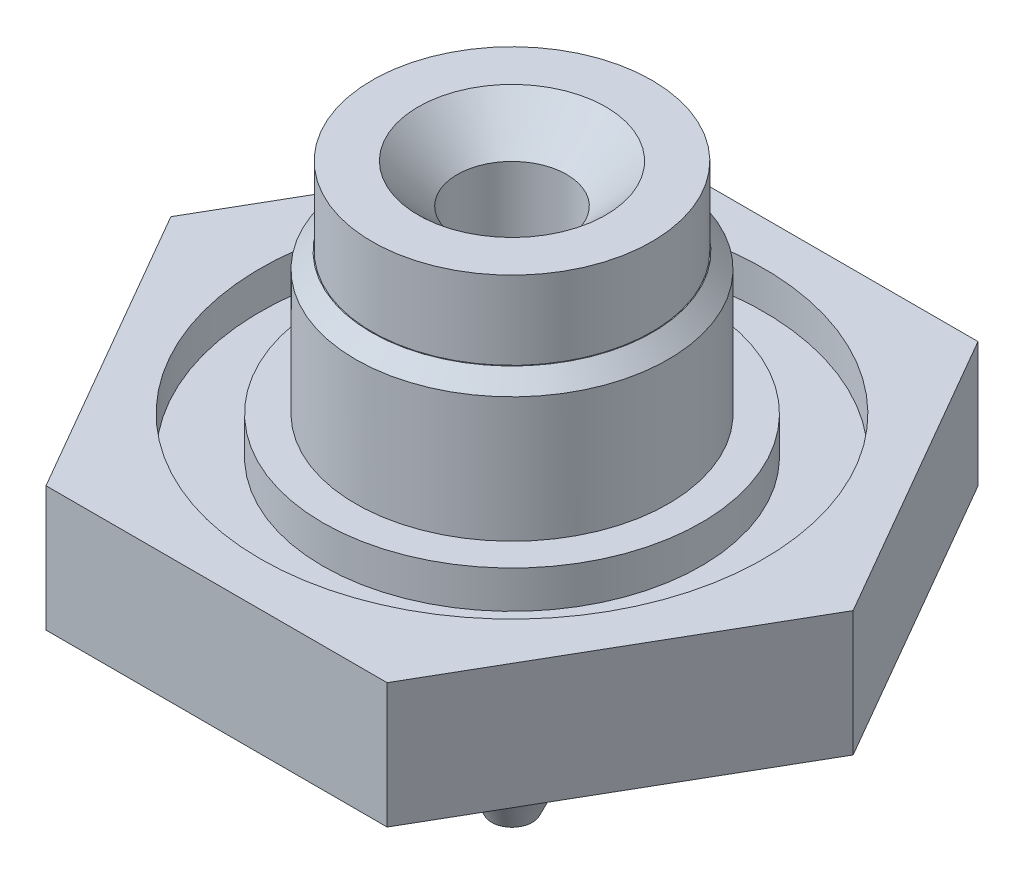
SolidWorks part; units mm, degrees
material "Acier allié inoxydable"
ref_plane "Front" through (0, 0, 0) normal (0, 0, 1) x (1, 0, 0)
ref_plane "Top" through (0, 0, 0) normal (0, 1, 0) x (1, 0, 0)
ref_plane "Right" through (0, 0, 0) normal (1, 0, 0) x (0, 0, -1)
sketch "Esquisse1" plane through (0, 0, 0) normal (0, 0, 1) x (1, 0, 0)
  line L0 (0, 0) -> (0, 18) construction
  line L1 (0.65, 0) -> (0.65, 2.5)
  line L2 (0.65, 2.5) -> (1.75, 3.6)
  line L3 (1.75, 3.6) -> (1.75, 16.75)
  line L4 (1.75, 16.75) -> (3, 18)
  line L5 (3, 18) -> (4.475, 18)
  line L7 (5, 11) -> (12.5, 11)
  line L8 (12.5, 11) -> (12.5, 7)
  line L10 (4.475, 18) -> (4.475, 15.5)
  line L11 (4.475, 15.5) -> (5, 15.5)
  line L12 (5, 15.5) -> (5, 11)
  line L13 (12.5, 7) -> (3.9142, 7)
  line L14 (3.9142, 7) -> (0.65, 0)
  dimension "D1" = 18
  dimension "D2" = 8.95
  dimension "D3" = 4
  dimension "D4" = 3.5
  dimension "D5" = 135
  dimension "D6" = 2.5
  dimension "D7" = 25
  dimension "D8" = 7
  dimension "D9" = 6
  dimension "D10" = 10
  dimension "D11" = 4.5
  dimension "D12" = 115
  dimension "D13" = 1.3
revolve "Révolution1" add sketch "Esquisse1" angle 360 about L0
chamfer "Chanfrein1" distance 0.5 angle 45 1 edges at (0, 15.5, -5)
sketch "Esquisse2" plane through (0, 11, 0) normal (0, 1, 0) x (1, 0, 0)
  line L0 (-10.9119, 0) -> (-5.456, 9.45)
  line L1 (-5.456, 9.45) -> (5.456, 9.45)
  line L2 (5.456, 9.45) -> (10.9119, 0)
  line L3 (10.9119, 0) -> (5.456, -9.45)
  line L4 (5.456, -9.45) -> (-5.456, -9.45)
  line L5 (-5.456, -9.45) -> (-10.9119, 0)
  line L6 (-8.1839, 4.725) -> (8.1839, -4.725) construction
  line L7 (8.1839, 4.725) -> (-8.1839, -4.725) construction
  circle A0 centre (0, 0) radius 12.5
  circle A1 centre (0, 0) radius 12.5 construction
  point P13 (0, 0)
  point P16 (0, 0)
  dimension "D1" = 120
  dimension "D2" = 120
  dimension "D3" = 18.9
extrude "Enlèv. mat.-Extru.1" cut sketch "Esquisse2" against normal through all
sketch "Esquisse3" plane through (0, 11, 0) normal (0, 1, 0) x (1, 0, 0)
  circle A0 centre (0, 0) radius 6.05
  circle A1 centre (0, 0) radius 8.05
  dimension "D1" = 12.1
  dimension "D2" = 2
extrude "Enlèv. mat.-Extru.2" cut sketch "Esquisse3" against normal blind 1.2
